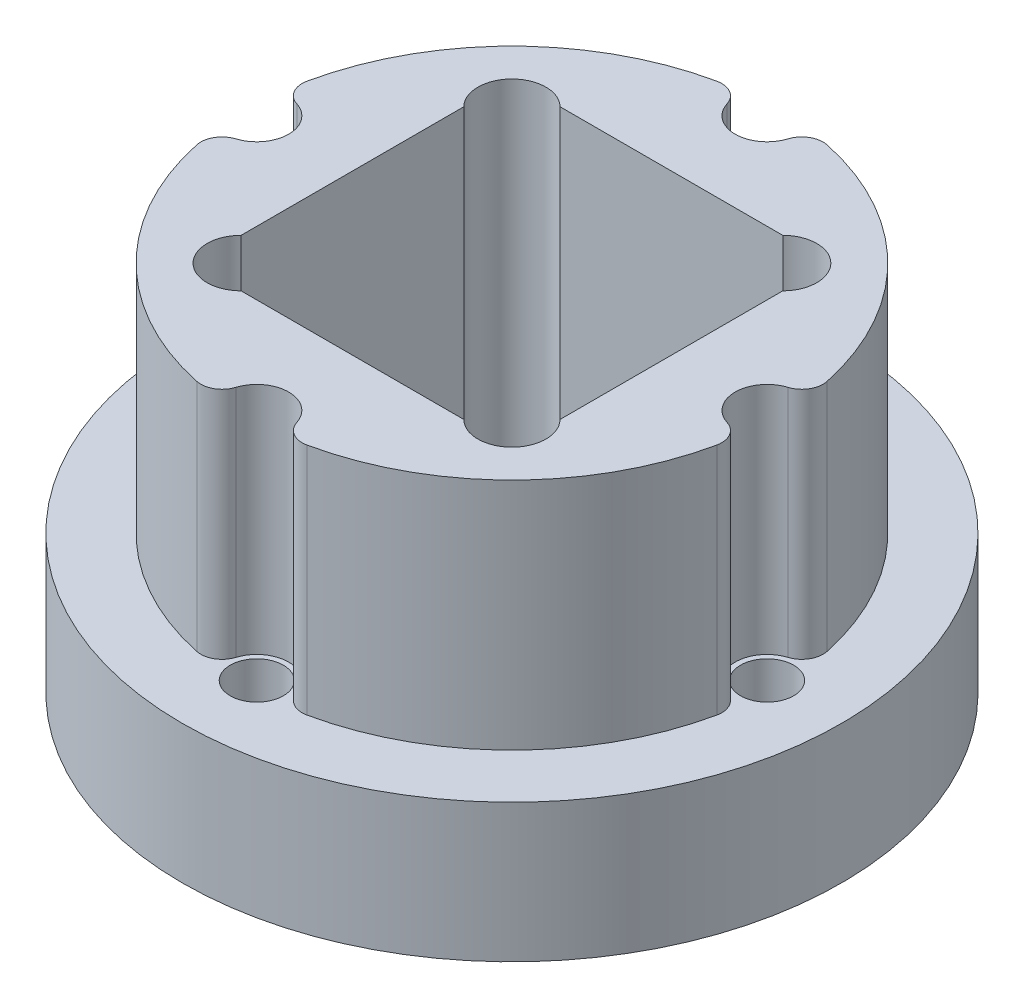
SolidWorks part; units mm, degrees
material "POM 乙缩醛共聚物"
ref_plane "前视基准面" through (0, 0, 0) normal (0, 0, 1) x (1, 0, 0)
ref_plane "上视基准面" through (0, 0, 0) normal (0, 1, 0) x (1, 0, 0)
ref_plane "右视基准面" through (0, 0, 0) normal (1, 0, 0) x (0, 0, -1)
sketch "草图1" plane through (0, 0, 0) normal (1, 0, 0) x (0, 0, -1)
  line L0 (0, 25.6073) -> (0, -21.6618) construction
  line L1 (-21.6239, 0) -> (23.4449, 0) construction
  line L2 (0, 0) -> (15.5, 0)
  line L3 (15.5, 0) -> (15.5, 6.5)
  line L4 (15.5, 6.5) -> (12.5, 6.5)
  line L5 (12.5, 6.5) -> (12.5, 17.5)
  line L6 (12.5, 17.5) -> (0, 17.5)
  line L7 (0, 17.5) -> (0, 0)
  dimension "D1" = 25
  dimension "D2" = 6.5
  dimension "D3" = 11
  dimension "D4" = 3
revolve "旋转1" add sketch "草图1" angle 360 about L0
sketch "草图2" plane through (0, 0, 0) normal (0, 1, 0) x (1, 0, 0)
  line L1 (-7.5, -7.5) -> (7.5, -7.5)
  line L2 (-7.5, -7.5) -> (-7.5, 7.5)
  line L3 (-7.5, 7.5) -> (7.5, 7.5)
  line L4 (7.5, -7.5) -> (7.5, 7.5)
  line L5 (-7.5, -7.5) -> (7.5, 7.5) construction
  line L6 (-7.5, 7.5) -> (7.5, -7.5) construction
  circle A0 centre (6.3686, -6.3686) radius 1.6
  circle A1 centre (-6.3686, -6.3686) radius 1.6
  circle A2 centre (-6.3686, 6.3686) radius 1.6
  circle A3 centre (6.3686, 6.3686) radius 1.6
  point P0 (0, 0)
  dimension "D2" = 3.2
  dimension "D1" = 15
extrude "切除-拉伸1" cut sketch "草图2" along normal through all contours A3 L3 A2 L2 A1 L1 A0 L4
sketch "草图3" plane through (0, 0, 0) normal (0, -1, 0) x (1, 0, 0)
  line L0 (-15.6002, 0) -> (15.5298, 0) construction
  line L1 (0, -17.3367) -> (0, 16.8067) construction
  point P5 (-12, 0)
  point P9 (0, 12)
  point P10 (12, 0)
  point P11 (0, -12)
  point P12 (0, 0)
  dimension "D1" = 12
  dimension "D2" = 4
hole_wizard "M3 螺纹孔1" positions "草图4" profile "草图5" tap size "M3" standard "GB" end condition up to next
sketch "草图4" plane through (0, 0, 0) normal (0, -1, 0) x (-1, 0, 0)
  point P0 (12, 0)
  point P3 (0, 12)
  point P6 (-12, 0)
  point P9 (0, -12)
sketch "草图5" plane through (-12, 0, 0) normal (1, 0, 0) x (0, 0, -1)
  line L0 (0, 0) -> (0, 17.5)
  line L1 (0, 17.5) -> (1.25, 17.5)
  line L2 (1.25, 17.5) -> (1.25, 0)
  line L5 (1.25, 0) -> (0, 0)
  line L11 (0, -6.35) -> (0, 107.95) construction
  dimension "通孔螺纹孔钻头直径" = 2.5
  dimension "通孔螺纹孔钻头深度" = 17.5
cosmetic thread "孔螺蚊线1" parameters "D2"=3
cosmetic thread "孔螺蚊线2" parameters "D2"=3
cosmetic thread "孔螺蚊线3" parameters "D2"=3
cosmetic thread "孔螺蚊线4" parameters "D2"=3
sketch "草图6" plane through (0, 17.5, 0) normal (0, 1, 0) x (1, 0, 0)
  line L0 (-12, 0) -> (12.5, 0) construction
  circle A0 centre (0, 0) radius 12.5 construction
  circle A1 centre (-12, 0) radius 1.5
  circle A2 centre (0, 12) radius 1.5
  circle A3 centre (12, 0) radius 1.5
  circle A4 centre (0, -12) radius 1.5
  point P16 (0, 0)
  dimension "D1" = 3
  dimension "D2" = 4
extrude "切除-拉伸2" cut sketch "草图6" against normal up to surface (11 mm away) up to face at (0, 6.5, 0)
fillet "圆角1" radius 1 8 edges at (12.4167, 12, 1.441) (12.4167, 12, -1.441) (1.441, 12, -12.4167) (-1.441, 12, -12.4167) (-12.4167, 12, -1.441) (-12.4167, 12, 1.441) (1.441, 12, 12.4167) (-1.441, 12, 12.4167)
move or copy body "实体-移动/复制1" [suppressed] bodies to move or copy 109
